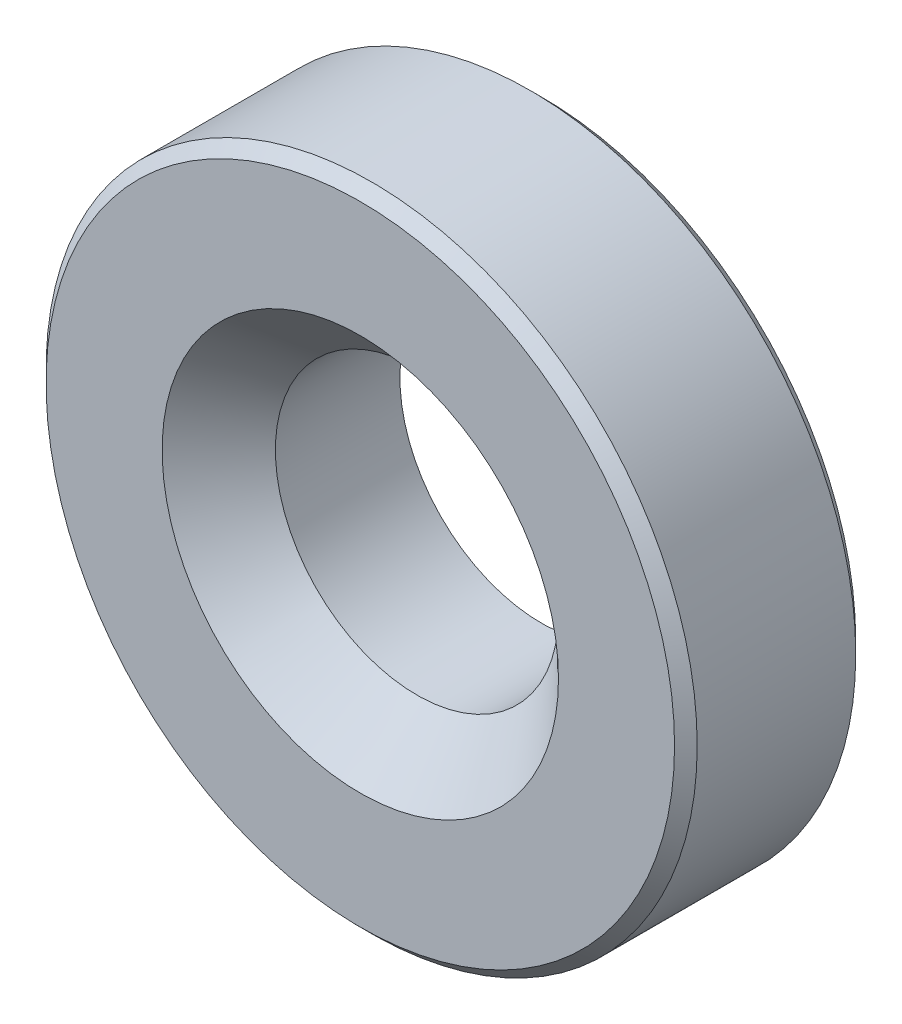
SolidWorks part; units mm, degrees
ref_plane "Front Plane" through (0, 0, 0) normal (0, 0, 1) x (1, 0, 0)
ref_plane "Top Plane" through (0, 0, 0) normal (0, 1, 0) x (1, 0, 0)
ref_plane "Right Plane" through (0, 0, 0) normal (1, 0, 0) x (0, 0, -1)
sketch "Sketch1" plane through (0, 0, 0) normal (0, 0, 1) x (1, 0, 0)
  circle A0 centre (0, 0) radius 57.5
  circle A1 centre (0, 0) radius 25
  dimension "D1" = 115
  dimension "D2" = 50
extrude "Boss-Extrude1" add sketch "Sketch1" along normal mid plane 32
chamfer "Chamfer1" distance 2 angle 45 2 edges at (57.5, 0, -16) (57.5, 0, 16)
chamfer "Chamfer2" distance 10 angle 45 1 edges at (25, 0, 16)
